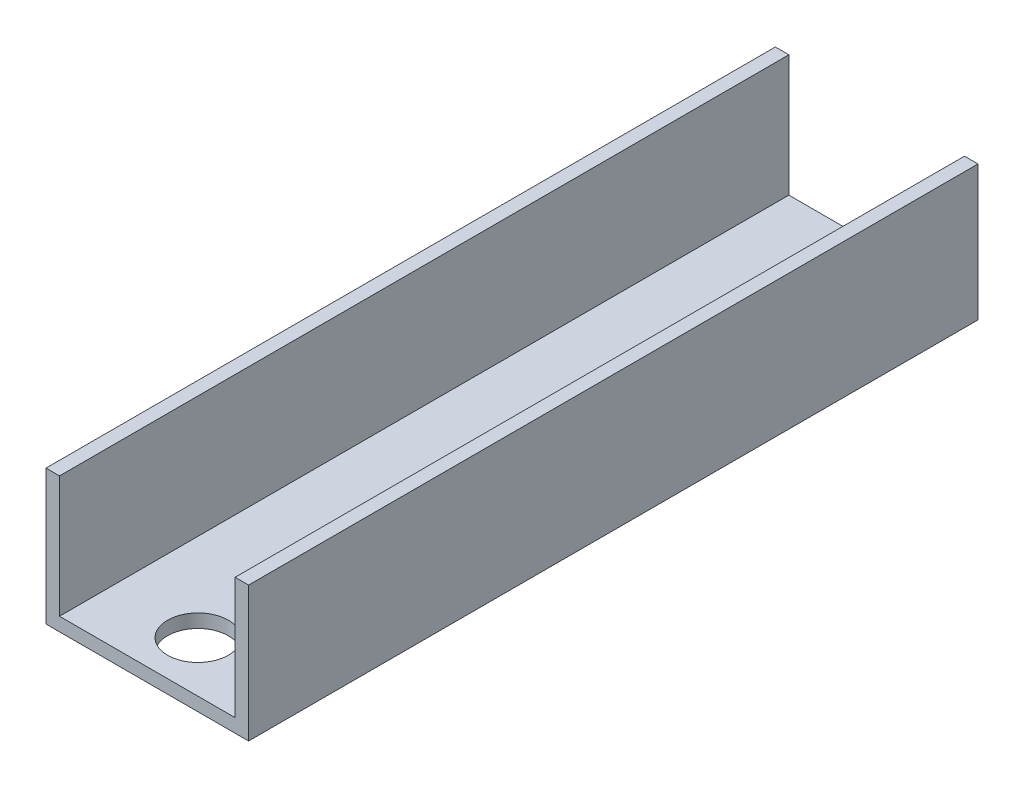
SolidWorks part; units mm, degrees
ref_plane "Спереди" through (0, 0, 0) normal (0, 0, 1) x (1, 0, 0)
ref_plane "Сверху" through (0, 0, 0) normal (0, 1, 0) x (1, 0, 0)
ref_plane "Справа" through (0, 0, 0) normal (1, 0, 0) x (0, 0, -1)
sketch "Эскиз1" plane through (0, 0, 0) normal (0, 0, 1) x (1, 0, 0)
  line L0 (0, 0) -> (0, 37.6785) construction
  line L1 (-6.5, 10) -> (-6.5, 1)
  line L2 (-7.5, 0) -> (7.5, 0)
  line L3 (-7.5, 0) -> (-7.5, 10)
  line L4 (-7.5, 10) -> (-6.5, 10)
  line L5 (7.5, 0) -> (7.5, 10)
  line L6 (-6.5, 1) -> (6.5, 1)
  line L7 (6.5, 1) -> (6.5, 10)
  line L8 (6.5, 10) -> (7.5, 10)
  dimension "D1" = 10
  dimension "D2" = 15
  dimension "D3" = 1
  dimension "D4" = 1
  dimension "D5" = 1
extrude "Вытянуть1" add sketch "Эскиз1" along normal blind 54
sketch "Эскиз2" plane through (0, 1, 0) normal (0, 1, 0) x (1, 0, 0)
  line L0 (0, 0) -> (0, -54) construction
  line L1 (0, -27) -> (16.6357, -27) construction
  line L2 (6.5, 0) -> (-6.5, 0) construction
  line L3 (6.5, -54) -> (-6.5, -54) construction
  circle A0 centre (0, -3.75) radius 2.25
  circle A1 centre (0, -50.25) radius 2.25
  dimension "D1" = 4.5
  dimension "D2" = 46.5
extrude "Вырез-Вытянуть1" cut sketch "Эскиз2" against normal blind 5
